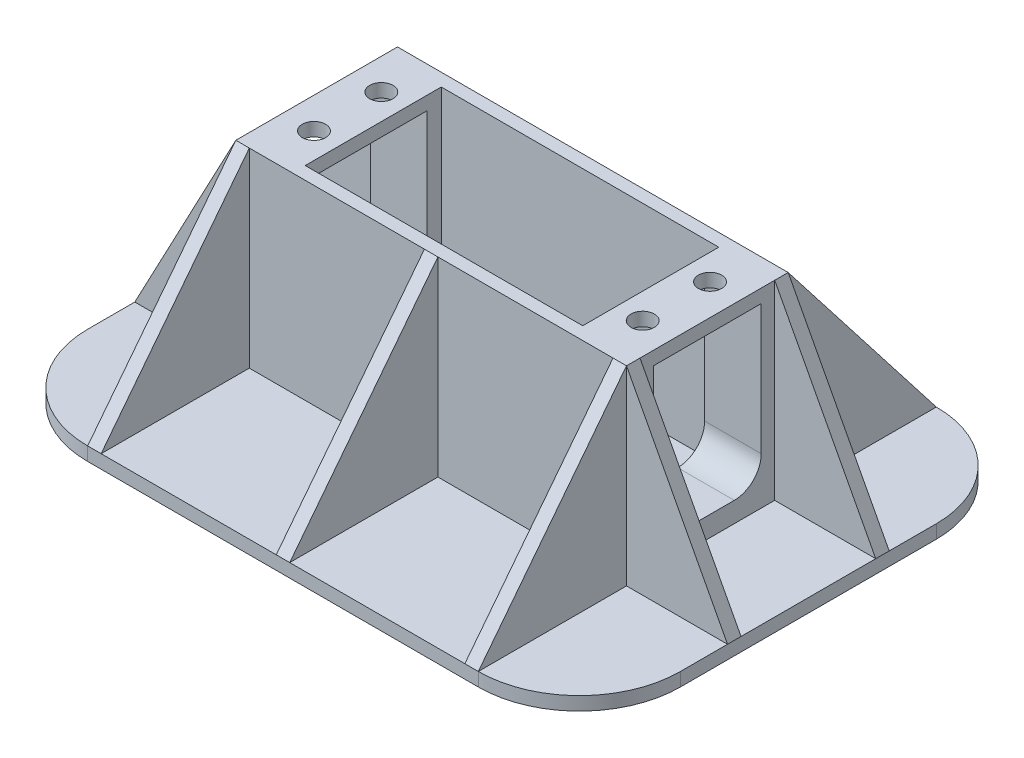
SolidWorks part; units mm, degrees
ref_plane "Front Plane" through (0, 0, 0) normal (0, 0, 1) x (1, 0, 0)
ref_plane "Top Plane" through (0, 0, 0) normal (0, 1, 0) x (1, 0, 0)
ref_plane "Right Plane" through (0, 0, 0) normal (1, 0, 0) x (0, 0, -1)
sketch "Sketch1" plane through (0, 0, 0) normal (0, 1, 0) x (1, 0, 0)
  line L1 (-29, -12) -> (29, -12)
  line L2 (-29, -12) -> (-29, 12)
  line L3 (-29, 12) -> (29, 12)
  line L4 (29, -12) -> (29, 12)
  line L5 (-29, -12) -> (29, 12) construction
  line L6 (-29, 12) -> (29, -12) construction
  point P0 (0, 0)
  dimension "D1" = 24
  dimension "D2" = 58
extrude "Boss-Extrude1" add sketch "Sketch1" along normal blind 28.3
sketch "Sketch2" plane through (0, 0, 0) normal (0, -1, 0) x (1, 0, 0)
  line L1 (-44, -34) -> (44, -34)
  line L2 (-44, -34) -> (-44, 34)
  line L3 (-44, 34) -> (44, 34)
  line L4 (44, -34) -> (44, 34)
  line L5 (-44, -34) -> (44, 34) construction
  line L6 (-44, 34) -> (44, -34) construction
  point P0 (0, 0)
  dimension "D1" = 68
  dimension "D2" = 88
extrude "Boss-Extrude2" add sketch "Sketch2" along normal blind 2
ref_plane "Plane2" through (29, 0, 0) normal (1, 0, 0) x (0, 0, -1)
ref_plane "Plane3" through (-29, 0, 0) normal (-1, 0, 0) x (0, 0, 1)
sketch "Sketch12" plane through (0, 28.3, 0) normal (0, 1, 0) x (1, 0, 0)
  line L1 (-20.6, -10.1) -> (20.6, -10.1)
  line L6 (-20.6, -10.1) -> (-20.6, 10.1)
  line L7 (-20.6, 10.1) -> (20.6, 10.1)
  line L8 (20.6, -10.1) -> (20.6, 10.1)
  line L9 (-20.6, -10.1) -> (20.6, 10.1) construction
  line L10 (-20.6, 10.1) -> (20.6, -10.1) construction
  point P0 (0, 0)
  point P2 (0, 0)
  dimension "D1" = 41.2
  dimension "D2" = 20.2
extrude "Cut-Extrude1" cut sketch "Sketch12" against normal blind 27.95
ref_plane "Plane4" through (-29, 0, 0) normal (-1, 0, 0) x (0, 0, 1)
sketch "Sketch14" plane through (-29, 0, 0) normal (-1, 0, 0) x (0, 0, 1)
  line L0 (-12, 28.3) -> (-12, 0)
  line L1 (-12, 0) -> (-34, 0)
  line L2 (-34, 0) -> (-12, 28.3)
  line L3 (12, 28.3) -> (12, 0)
  line L4 (12, 0) -> (34, 0)
  line L5 (34, 0) -> (12, 28.3)
extrude "Boss-Extrude6" add sketch "Sketch14" against normal blind 2
pattern_linear "LPattern2" count 3 spacing 28 along (1, 0, 0) of "Boss-Extrude6"
ref_plane "Plane5" through (0, 0, -12) normal (0, 0, -1) x (-1, 0, 0)
sketch "Sketch16" plane through (0, 0, -12) normal (0, 0, -1) x (-1, 0, 0)
  line L0 (-29, 28.3) -> (-44, 0)
  line L1 (-44, 0) -> (-29, 0)
  line L2 (-29, 0) -> (-29, 28.3)
  line L3 (29, 28.3) -> (29, 0)
  line L4 (29, 0) -> (44, 0)
  line L5 (44, 0) -> (29, 28.3)
extrude "Boss-Extrude7" add sketch "Sketch16" against normal blind 2
pattern_linear "LPattern3" count 2 spacing 22 along (0, 0, 1) of "Boss-Extrude7"
sketch "Sketch17" plane through (0, 28.3, 0) normal (0, 1, 0) x (1, 0, 0)
  circle A0 centre (-24.4, 5) radius 1
  circle A1 centre (-24.4, -5) radius 1
  circle A2 centre (24.4, -5) radius 1
  circle A3 centre (24.4, 5) radius 1
  dimension "D1" = 2
  dimension "D2" = 2
  dimension "D3" = 2
  dimension "D4" = 2
extrude "Cut-Extrude2" cut sketch "Sketch17" against normal blind 10
hole_wizard "#8-32 Tapped Hole1" positions "3DSketch1" profile "Sketch18" tap size "#8-32" standard "ANSI Inch"
sketch3d "3DSketch1"
  line L0 (-24.4, 18.3, -5) -> (-24.4, 28.3, -5) construction
  line L1 (-24.4, 18.3, 5) -> (-24.4, 28.3, 5) construction
  line L2 (24.4, 18.3, -5) -> (24.4, 28.3, -5) construction
  line L3 (24.4, 18.3, 5) -> (24.4, 28.3, 5) construction
  point P0 (-24.4, 28.3, -5)
  point P4 (-24.4, 28.3, 5)
  point P8 (24.4, 28.3, -5)
  point P12 (24.4, 28.3, 5)
cosmetic thread "Hole Thread1" parameters "D1"=10.75, "D2"=4.1656
cosmetic thread "Hole Thread2" parameters "D1"=10.75, "D2"=4.1656
cosmetic thread "Hole Thread3" parameters "D1"=10.75, "D2"=4.1656
cosmetic thread "Hole Thread4" parameters "D1"=10.75, "D2"=4.1656
sketch "Sketch18" plane through (-24.4, 28.3, -5) normal (1, 0, 0) x (0, 0, 1)
  line L0 (0, 0) -> (0, 13.0378)
  line L1 (0, 13.0378) -> (1.7272, 12)
  line L2 (1.7272, 12) -> (1.7272, 0)
  line L5 (1.7272, 0) -> (0, 0)
  line L10 (0, 13.0378) -> (-1.7272, 12) construction
  line L11 (0, -6.35) -> (0, 107.95) construction
  dimension "Tap Drill Dia." = 3.4544
  dimension "Tap Drill Depth" = 12
  dimension "Drill Angle" = 118
fillet "Fillet1" radius 15 2 edges at (-44, -1, 34) (-36.5, 0, 34)
fillet "Fillet2" radius 15 2 edges at (36.5, 0, 34) (44, -1, 34)
fillet "Fillet3" radius 15 2 edges at (44, -1, -34) (36.5, 0, -34)
fillet "Fillet5" radius 15 2 edges at (-36.5, 0, -34) (-44, -1, -34)
sketch "Sketch20" plane through (-29, 0, 0) normal (-1, 0, 0) x (0, 0, 1)
  line L0 (-8, 3) -> (8, 3)
  line L1 (-8, 3) -> (-8, 26.3)
  line L2 (8, 3) -> (8, 26.3)
  line L3 (-8, 26.3) -> (8, 26.3)
  line L4 (-10, 28.3) -> (10, 28.3) construction
  line L5 (-10, 0) -> (10, 0) construction
  line L6 (-10, 28.3) -> (-10, 0) construction
  line L7 (10, 28.3) -> (10, 0) construction
  dimension "D1" = 2
  dimension "D2" = 3
  dimension "D3" = 2
  dimension "D4" = 2
extrude "Cut-Extrude3" cut sketch "Sketch20" against normal blind 10
sketch "Sketch21" plane through (29, 0, 0) normal (1, 0, 0) x (0, 0, -1)
  line L0 (-10, 28.3) -> (10, 28.3) construction
  line L1 (-8, 26.3) -> (8, 26.3)
  line L2 (-8, 26.3) -> (-8, 3)
  line L3 (-8, 3) -> (8, 3)
  line L4 (8, 26.3) -> (8, 3)
  line L5 (-10, 0) -> (10, 0) construction
  line L6 (-10, 0) -> (-10, 28.3) construction
  line L7 (10, 0) -> (10, 28.3) construction
  point P6 (0, 28.3)
  dimension "D1" = 2
  dimension "D2" = 3
  dimension "D3" = 2
  dimension "D4" = 2
extrude "Cut-Extrude4" cut sketch "Sketch21" against normal blind 10
fillet "Fillet6" radius 4 1 edges at (24.8, 3, 8)
fillet "Fillet7" radius 4 1 edges at (24.8, 3, -8)
fillet "Fillet8" radius 4 1 edges at (-24.8, 3, -8)
fillet "Fillet9" radius 4 1 edges at (-24.8, 3, 8)
